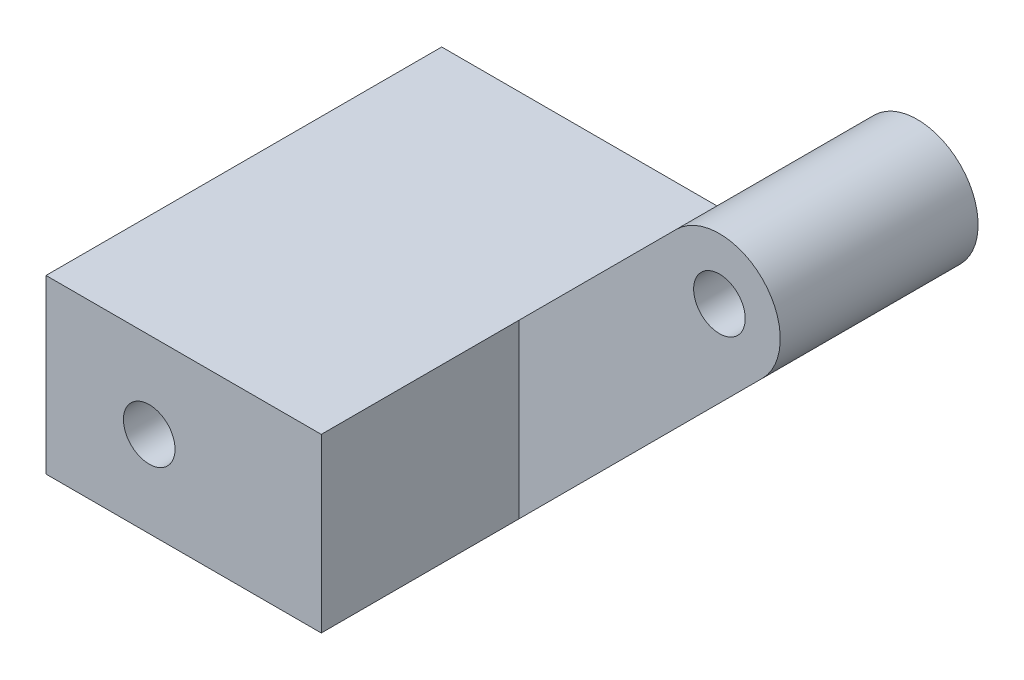
SolidWorks part; units mm, degrees
ref_plane "前视基准面" through (0, 0, 0) normal (0, 0, 1) x (1, 0, 0)
ref_plane "上视基准面" through (0, 0, 0) normal (0, 1, 0) x (1, 0, 0)
ref_plane "右视基准面" through (0, 0, 0) normal (1, 0, 0) x (0, 0, -1)
other "Configuration Table"
sketch "草图1" plane through (0, 0, 0) normal (0, 0, 1) x (1, 0, 0)
  line L0 (16, 0) -> (30.1421, 14.1421)
  line L1 (0, 0) -> (16, 0)
  line L2 (0, 0) -> (0, 10)
  line L3 (0, 10) -> (16, 10)
  line L5 (16, 10) -> (25.1421, 19.1421)
  circle A0 centre (6, 5) radius 1.5
  arc A1 (30.1421, 14.1421) -> (25.1421, 19.1421) centre (27.6421, 16.6421) ccw
  arc A2 (30.1421, 14.1421) -> (25.1421, 19.1421) centre (27.6421, 16.6421) ccw
  circle A3 centre (27.6421, 16.6421) radius 1.5
  dimension "D3" = 3
  dimension "D10" = 3.5355
  dimension "D6" = 3
  dimension "D1" = 10
  dimension "D2" = 16
  dimension "D4" = 5
  dimension "D5" = 6
  dimension "D7" = 20
  dimension "D8" = 135
  dimension "D9" = 225
extrude "凸台-拉伸2" add sketch "草图1" along normal blind 23 contours L0 A1 L5 L3 L2 L1 A3 A0
sketch "草图2" plane through (0, 0, 23) normal (0, 0, 1) x (1, 0, 0)
  line L1 (16, 0) -> (33.0715, 0)
  line L2 (16, 0) -> (16, 21.5703)
  line L3 (16, 21.5703) -> (33.0715, 21.5703)
  line L4 (33.0715, 0) -> (33.0715, 21.5703)
extrude "切除-拉伸1" cut sketch "草图2" against normal blind 11.5
